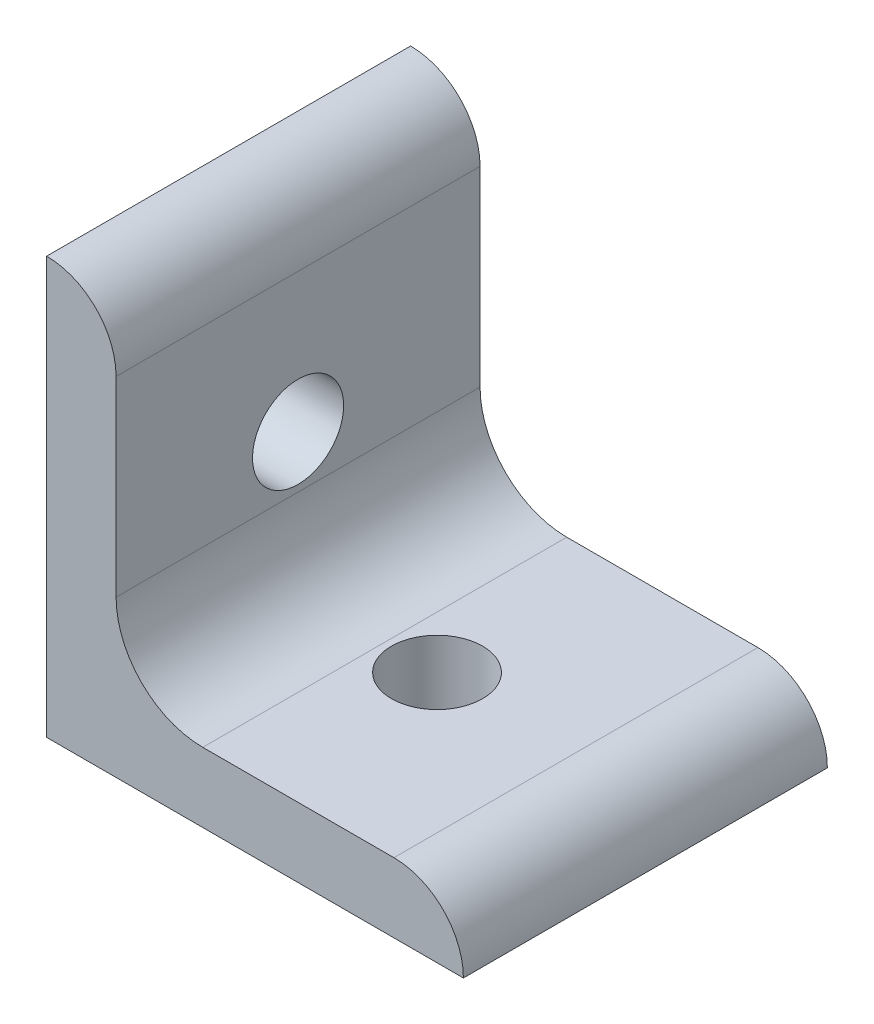
SolidWorks part; units mm, degrees
ref_plane "Front Plane" through (0, 0, 0) normal (0, 0, 1) x (1, 0, 0)
ref_plane "Top Plane" through (0, 0, 0) normal (0, 1, 0) x (1, 0, 0)
ref_plane "Right Plane" through (0, 0, 0) normal (1, 0, 0) x (0, 0, -1)
sketch "Sketch1" plane through (0, 0, 0) normal (0, 0, 1) x (1, 0, 0)
  line L0 (0, 0) -> (0, 38.1)
  line L1 (6.35, 31.75) -> (6.35, 38.1) construction
  line L2 (6.35, 31.75) -> (6.35, 14.2748)
  line L3 (14.2748, 6.35) -> (31.75, 6.35)
  line L4 (6.35, 38.1) -> (0, 38.1) construction
  line L5 (38.1, 0) -> (0, 0)
  line L6 (31.75, 6.35) -> (38.1, 6.35) construction
  line L7 (38.1, 6.35) -> (38.1, 0) construction
  arc A0 (6.35, 31.75) -> (0, 38.1) centre (0, 31.75) ccw
  arc A1 (38.1, 0) -> (31.75, 6.35) centre (31.75, 0) ccw
  arc A2 (6.35, 14.2748) -> (14.2748, 6.35) centre (14.2748, 14.2748) ccw
  point P10 (6.35, 34.925)
  dimension "E" = 7.9248
  dimension "D" = 6.35
  dimension "C" = 38.1
  dimension "B" = 38.1
extrude "Boss-Extrude1" add sketch "Sketch1" along normal mid plane 33.274
sketch "Sketch2" plane through (0, 0, 0) normal (0, 1, 0) x (1, 0, 0)
  line L0 (0, 0) -> (19.05, 0) construction
  circle A0 centre (19.05, 0) radius 4.1656
  dimension "D1" = 19.05
  dimension "E" = 8.3312
extrude "Cut-Extrude1" cut sketch "Sketch2" along normal through all
sketch "Sketch3" plane through (0, 0, 0) normal (1, 0, 0) x (0, 0, -1)
  line L0 (0, 0) -> (0, 19.05) construction
  circle A0 centre (0, 19.05) radius 4.1656
  dimension "D1" = 19.05
  dimension "E" = 8.3312
extrude "Cut-Extrude2" cut sketch "Sketch3" along normal through all
equation "\"E@Sketch3\" = \"E@Sketch2\""
equation "\"D1@Sketch3\" = \"D1@Sketch2\""
